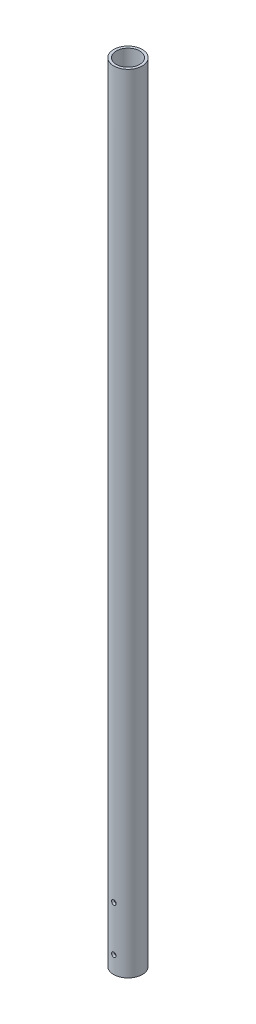
SolidWorks part; units mm, degrees
ref_plane "Front Plane" through (0, 0, 0) normal (0, 0, 1) x (1, 0, 0)
ref_plane "Top Plane" through (0, 0, 0) normal (0, 1, 0) x (1, 0, 0)
ref_plane "Right Plane" through (0, 0, 0) normal (1, 0, 0) x (0, 0, -1)
sketch "Sketch1" plane through (0, 0, 0) normal (0, 1, 0) x (1, 0, 0)
  circle A0 centre (0, 0) radius 21.082
  circle A1 centre (0, 0) radius 17.272
  dimension "D1" = 34.544
  dimension "1.66" = 42.164
extrude "Boss-Extrude1" add sketch "Sketch1" along normal blind 1160.4625
ref_plane "Plane1" through (0, 0, 21.082) normal (0, 0, 1) x (1, 0, 0)
sketch "Sketch2" plane through (0, 0, 21.082) normal (0, 0, 1) x (1, 0, 0)
  line L0 (-21.082, 1.5875) -> (21.082, 1.5875) construction
  line L1 (-21.082, 1160.4625) -> (-21.082, 0) construction
  line L2 (-21.082, 0) -> (21.082, 0) construction
  line L3 (-21.082, 103.1875) -> (21.082, 103.1875) construction
  line L4 (21.082, 0) -> (21.082, 1160.4625) construction
  point P0 (0, 25.4)
  point P1 (0, 92.075)
  dimension "D1" = 1.5875
  dimension "D2" = 66.675
  dimension "D3" = 25.4
  dimension "D4" = 101.6
hole_wizard "1/4 Clearance Hole1" positions "Sketch3" profile "Sketch4" hole size "1/4" standard "ANSI Inch" end condition through all
sketch "Sketch3" plane through (0, 0, 21.082) normal (0, 0, 1) x (1, 0, 0)
  point P0 (0, 25.4)
  point P3 (0, 92.075)
sketch "Sketch4" plane through (0, 25.4, 21.082) normal (1, 0, 0) x (0, -1, 0)
  line L0 (0, 0) -> (0, 42.164)
  line L1 (0, 42.164) -> (3.3782, 42.164)
  line L2 (3.3782, 42.164) -> (3.3782, 0)
  line L5 (3.3782, 0) -> (0, 0)
  line L11 (0, -6.35) -> (0, 107.95) construction
  dimension "Thru Hole Dia." = 6.7564
  dimension "Thru Hole Depth" = 42.164
